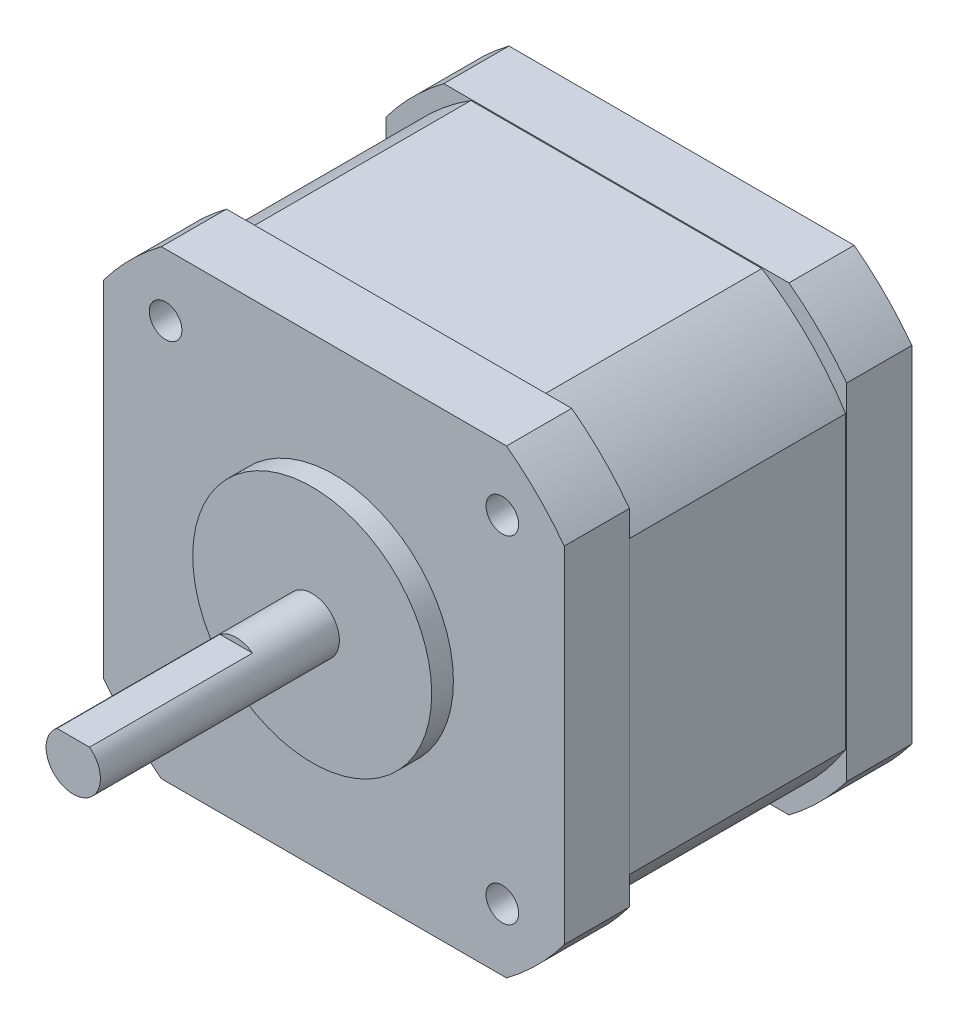
SolidWorks part; units mm, degrees
material "Plain Carbon Steel"
ref_plane "Front" through (0, 0, 0) normal (0, 0, 1) x (1, 0, 0)
ref_plane "Top" through (0, 0, 0) normal (0, 1, 0) x (1, 0, 0)
ref_plane "Right" through (0, 0, 0) normal (1, 0, 0) x (0, 0, -1)
sketch "Sketch1" plane through (0, 0, 0) normal (0, 0, 1) x (1, 0, 0)
  circle A0 centre (0, 0) radius 2.5
  dimension "D1" = 5
extrude "Boss-Extrude1" add sketch "Sketch1" along normal blind 24
sketch "Sketch2" plane through (0, 0, 0) normal (0, 0, -1) x (-1, 0, 0)
  circle A0 centre (0, 0) radius 11
  dimension "D1" = 22
extrude "Boss-Extrude2" add sketch "Sketch2" against normal blind 2
sketch "Sketch3" plane through (0, 0, 0) normal (0, 0, -1) x (-1, 0, 0)
  line L1 (21.209, -21.209) -> (-21.209, -21.209)
  line L2 (21.209, -21.209) -> (21.209, 21.209)
  line L3 (21.209, 21.209) -> (-21.209, 21.209)
  line L4 (-21.209, -21.209) -> (-21.209, 21.209)
  line L5 (21.209, -21.209) -> (-21.209, 21.209) construction
  line L6 (21.209, 21.209) -> (-21.209, -21.209) construction
  point P0 (0, 0)
  dimension "D1" = 42.418
extrude "Boss-Extrude3" add sketch "Sketch3" along normal blind 32
sketch "Sketch4" plane through (0, 0, -32) normal (0, 0, -1) x (-1, 0, 0)
  line L0 (-21.209, -15.888) -> (-21.209, -21.209)
  line L1 (15.888, -21.209) -> (21.209, -21.209)
  line L2 (21.209, 15.888) -> (21.209, 21.209)
  line L3 (-15.888, 21.209) -> (-21.209, 21.209)
  line L4 (-21.209, 21.209) -> (-21.209, -21.209)
  line L5 (-21.209, -21.209) -> (21.209, -21.209)
  line L6 (21.209, -21.209) -> (21.209, 21.209)
  line L7 (21.209, 21.209) -> (-21.209, 21.209)
  line L8 (-21.209, 21.209) -> (-21.209, 15.888)
  line L9 (-21.209, -21.209) -> (-15.888, -21.209)
  line L10 (21.209, -21.209) -> (21.209, -15.888)
  line L11 (21.209, 21.209) -> (15.888, 21.209)
  arc A0 (-21.209, -15.888) -> (-15.888, -21.209) centre (0, 0) ccw
  arc A1 (15.888, -21.209) -> (21.209, -15.888) centre (0, 0) ccw
  arc A2 (21.209, 15.888) -> (15.888, 21.209) centre (0, 0) ccw
  arc A3 (-15.888, 21.209) -> (-21.209, 15.888) centre (0, 0) ccw
  dimension "D2" = 26.5
  dimension "D1" = 0
extrude "Cut-Extrude1" cut sketch "Sketch4" against normal through all
hole_wizard "M3x0.5 Tapped Hole1" positions "Sketch6" profile "Sketch5" tap size "M3x0.5" standard "ANSI Metric"
sketch "Sketch6" plane through (0, 0, 0) normal (0, 0, 1) x (1, 0, 0)
  line L0 (-16.1632, 0) -> (0, 0) construction
  line L1 (0, 0) -> (0, 15.0764) construction
  point P0 (-15.5, 15.5)
  point P11 (-15.5, -15.5)
  point P12 (15.5, -15.5)
  point P13 (15.5, 15.5)
  dimension "D1" = 31
  dimension "D2" = 31
sketch "Sketch5" plane through (-15.5, 15.5, 0) normal (1, 0, 0) x (0, -1, 0)
  line L0 (0, 0) -> (0, 8.2511)
  line L1 (0, 8.2511) -> (1.25, 7.5)
  line L2 (1.25, 7.5) -> (1.25, 6)
  line L3 (1.25, 6) -> (1.5, 6)
  line L4 (1.5, 6) -> (1.5, 0)
  line L5 (1.5, 0) -> (0, 0)
  line L10 (0, 8.2511) -> (-1.25, 7.5) construction
  line L11 (0, -6.35) -> (0, 107.95) construction
  dimension "Tap Drill Dia." = 2.5
  dimension "Tap Drill Depth" = 7.5
  dimension "Thread Major Dia." = 3
  dimension "Thread Depth" = 6
  dimension "Drill Angle" = 118
sketch "Sketch7" plane through (0, 0, 24) normal (0, 0, 1) x (1, 0, 0)
  line L0 (-1.5, 2) -> (1.5, 2)
  circle A0 centre (0, 0) radius 2.5 construction
  circle A1 centre (0, 0) radius 2.5 construction
  arc A2 (1.5, 2) -> (-1.5, 2) centre (0, 0) ccw
  dimension "D1" = 4.5
extrude "Cut-Extrude2" cut sketch "Sketch7" against normal blind 15
ref_plane "Plane1" through (0, 0, -16) normal (0, 0, 1) x (1, 0, 0)
sketch "Sketch8" plane through (0, 0, -16) normal (0, 0, 1) x (1, 0, 0)
  line L0 (-13.3944, 21.109) -> (13.3944, 21.109)
  line L1 (-5.7152, 0) -> (0, 0) construction
  line L2 (0, 0) -> (0, 8.4579) construction
  line L3 (-15.888, 21.209) -> (15.888, 21.209) construction
  line L4 (-13.3944, -21.109) -> (13.3944, -21.109)
  line L5 (-21.109, 13.3944) -> (-21.109, -13.3944)
  line L6 (-21.209, -15.888) -> (-21.209, 15.888) construction
  line L7 (21.109, 13.3944) -> (21.109, -13.3944)
  line L12 (15.888, 21.209) -> (-15.888, 21.209)
  line L13 (-21.209, 15.888) -> (-21.209, -15.888)
  line L14 (-15.888, -21.209) -> (15.888, -21.209)
  line L15 (21.209, -15.888) -> (21.209, 15.888)
  line L16 (15.888, 21.209) -> (-15.888, 21.209)
  line L17 (-21.209, 15.888) -> (-21.209, -15.888)
  line L18 (-15.888, -21.209) -> (15.888, -21.209)
  line L19 (21.209, -15.888) -> (21.209, 15.888)
  arc A0 (-13.3944, 21.109) -> (-21.109, 13.3944) centre (0, 0) ccw
  arc A1 (-21.109, -13.3944) -> (-13.3944, -21.109) centre (0, 0) ccw
  arc A2 (21.109, 13.3944) -> (13.3944, 21.109) centre (0, 0) ccw
  arc A3 (13.3944, -21.109) -> (21.109, -13.3944) centre (0, 0) ccw
  arc A8 (-15.888, 21.209) -> (-21.209, 15.888) centre (0, 0) ccw
  arc A9 (-15.888, 21.209) -> (-21.209, 15.888) centre (0, 0) ccw
  arc A10 (-21.209, -15.888) -> (-15.888, -21.209) centre (0, 0) ccw
  arc A11 (-21.209, -15.888) -> (-15.888, -21.209) centre (0, 0) ccw
  arc A12 (15.888, -21.209) -> (21.209, -15.888) centre (0, 0) ccw
  arc A13 (15.888, -21.209) -> (21.209, -15.888) centre (0, 0) ccw
  arc A14 (21.209, 15.888) -> (15.888, 21.209) centre (0, 0) ccw
  arc A15 (21.209, 15.888) -> (15.888, 21.209) centre (0, 0) ccw
  dimension "D1" = 50
  dimension "D2" = 0.1
  dimension "D3" = 0.1
  dimension "D4" = 0
extrude "Cut-Extrude3" cut sketch "Sketch8" against normal mid plane 20
